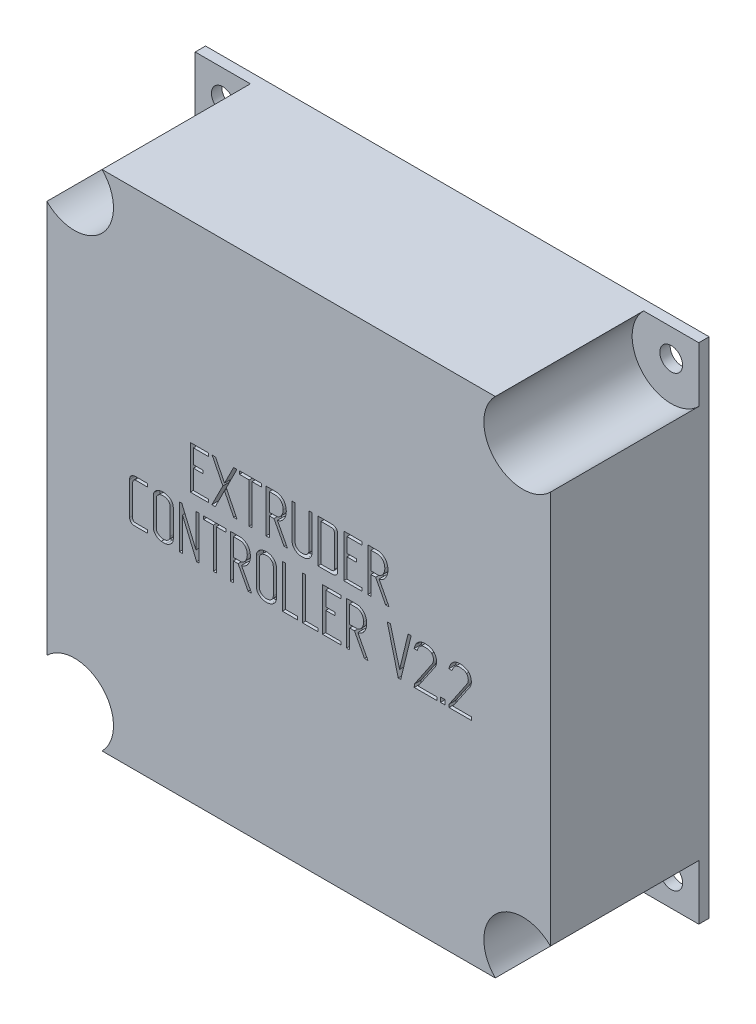
SolidWorks part; units mm, degrees
ref_plane "Front Plane" through (0, 0, 0) normal (0, 0, 1) x (1, 0, 0)
ref_plane "Top Plane" through (0, 0, 0) normal (0, 1, 0) x (1, 0, 0)
ref_plane "Right Plane" through (0, 0, 0) normal (1, 0, 0) x (0, 0, -1)
ref_plane "Plane1" through (0, 0, 23) normal (0, 0, 1) x (1, 0, 0)
sketch "Sketch1" plane through (0, 0, 23) normal (0, 0, 1) x (1, 0, 0)
  line L0 (32.2371, 36.0676) -> (32.2371, 45.1403)
  line L1 (32.2371, 45.1403) -> (11.9925, 45.1403)
  line L2 (11.9925, 45.1403) -> (11.9925, 36.0723)
  line L3 (11.9925, 36.0676) -> (32.2371, 36.0676)
  spline S0 degree 3 poles (11.9925, 36.0676) (11.9925, 36.0692) (11.9925, 36.0708) (11.9925, 36.0723) knots 0.369742 0.369742 0.369742 0.369742 0.369966 0.369966 0.369966 0.369966
extrude "Boss-Extrude1" add sketch "Sketch1" against normal blind 1
sketch "Sketch2" plane through (32.2371, 0, 0) normal (1, 0, 0) x (0, 0, -1)
  line L0 (-23, 36.0676) -> (-23, 45.1403)
  line L1 (-23, 45.1403) -> (-22, 45.1403)
  line L2 (-22, 45.1403) -> (-22, 36.0676)
  line L3 (-22, 36.0676) -> (-23, 36.0676)
extrude "Boss-Extrude2" add sketch "Sketch2" along normal blind 1.0059
sketch "Sketch3" plane through (0, 36.0676, 0) normal (0, -1, 0) x (1, 0, 0)
  line L0 (33.243, 22) -> (11.9925, 22)
  line L1 (11.9925, 22) -> (11.9925, 23)
  line L2 (11.9925, 23) -> (33.243, 23)
  line L3 (33.243, 23) -> (33.243, 22)
extrude "Boss-Extrude3" add sketch "Sketch3" along normal blind 4.7542
sketch "Sketch4" plane through (33.243, 0, 0) normal (1, 0, 0) x (0, 0, -1)
  line L0 (-23, 31.3134) -> (-23, 45.1403)
  line L1 (-23, 45.1403) -> (-22, 45.1403)
  line L2 (-22, 45.1403) -> (-22, 31.3134)
  line L3 (-22, 31.3134) -> (-23, 31.3134)
extrude "Boss-Extrude4" add sketch "Sketch4" along normal blind 20.0076
sketch "Sketch5" plane through (0, 31.3134, 0) normal (0, -1, 0) x (1, 0, 0)
  line L0 (11.9925, 22) -> (11.9925, 23)
  line L1 (11.9925, 23) -> (53.2506, 23)
  line L2 (53.2506, 23) -> (53.2506, 22)
  line L3 (53.2506, 22) -> (11.9925, 22)
extrude "Boss-Extrude5" add sketch "Sketch5" along normal blind 0.7109
sketch "Sketch6" plane through (0, 0, 22) normal (0, 0, -1) x (-1, 0, 0)
  line L0 (-53.2506, 45.1403) -> (-11.9925, 45.1403)
  line L1 (-11.9925, 45.1403) -> (-11.9925, 30.6025)
  line L2 (-11.9925, 30.6025) -> (-53.2506, 30.6025)
  line L3 (-53.2506, 30.6025) -> (-53.2506, 45.1403)
extrude "Boss-Extrude6" add sketch "Sketch6" along normal blind 22
sketch "Sketch7" plane through (0, 0, 23) normal (0, 0, 1) x (1, 0, 0)
  spline S0 degree 3 poles (32.2371, 41.6388) (32.2371, 41.7904) (32.2371, 41.9419) (32.2371, 42.0935) knots 0.441044 0.441044 0.441044 0.441044 0.460629 0.460629 0.460629 0.460629
  spline S1 degree 3 poles (32.919, 41.6388) (32.6917, 41.6388) (32.4644, 41.6388) (32.2371, 41.6388) knots 0.155394 0.155394 0.155394 0.155394 0.184772 0.184772 0.184772 0.184772
  spline S2 degree 3 poles (34.3747, 38.8919) (33.8895, 39.8075) (33.4042, 40.7232) (32.919, 41.6388) knots 0.02146 0.02146 0.02146 0.02146 0.155394 0.155394 0.155394 0.155394
  spline S3 degree 3 poles (34.8728, 38.8919) (34.7068, 38.8919) (34.5408, 38.8919) (34.3747, 38.8919) knots 0 0 0 0 0.02146 0.02146 0.02146 0.02146
  spline S4 degree 3 poles (33.4171, 41.6679) (33.9024, 40.7425) (34.3876, 39.8172) (34.8728, 38.8919) knots 0.86496 0.86496 0.86496 0.86496 1 1 1 1
  spline S5 degree 3 poles (33.243, 45.1403) (33.4075, 45.1403) (33.5671, 45.1064) (33.7267, 45.0387) (34.3732, 44.7644) (34.7036, 44.2262) (34.7036, 43.0123) (34.5875, 42.64) (34.3602, 42.3014) (34.1112, 41.9306) (33.7992, 41.7211) (33.4171, 41.6679) knots 0.654813 0.654813 0.654813 0.654813 0.676249 0.676249 0.676249 0.768188 0.768188 0.814433 0.814433 0.814433 0.86496 0.86496 0.86496 0.86496
  spline S6 degree 3 poles (32.2371, 45.1403) (32.5724, 45.1403) (32.9077, 45.1403) (33.243, 45.1403) knots 0.611475 0.611475 0.611475 0.611475 0.654813 0.654813 0.654813 0.654813
  spline S7 degree 3 poles (32.2371, 44.6857) (32.2371, 44.8372) (32.2371, 44.9888) (32.2371, 45.1403) knots 0.572305 0.572305 0.572305 0.572305 0.59189 0.59189 0.59189 0.59189
  spline S8 degree 3 poles (34.249, 43.4138) (34.249, 43.8103) (34.1329, 44.1295) (33.8911, 44.3762) (33.6923, 44.5789) (33.4703, 44.6857) (33.214, 44.6857) (32.8884, 44.6857) (32.5627, 44.6857) (32.2371, 44.6857) knots 0 0 0 0 0.128223 0.128223 0.128223 0.221431 0.221431 0.221431 0.340112 0.340112 0.340112 0.340112
  spline S9 degree 3 poles (32.2371, 42.0935) (32.5885, 42.0935) (32.94, 42.0935) (33.2914, 42.0935) (33.4848, 42.0935) (33.6831, 42.1999) (33.8814, 42.4175) (34.1209, 42.6803) (34.249, 43.0075) (34.249, 43.4138) knots 0.655283 0.655283 0.655283 0.655283 0.783468 0.783468 0.783468 0.867727 0.867727 0.867727 1 1 1 1
extrude "Cut-Extrude1" cut sketch "Sketch7" against normal blind 1
sketch "Sketch8" plane through (0, 0, 23) normal (0, 0, 1) x (1, 0, 0)
  spline S0 degree 3 poles (14.5558, 31.0571) (14.5558, 30.9104) (14.5558, 30.7637) (14.5558, 30.617) knots 0.97892 0.97892 0.97892 0.97892 1 1 1 1
  spline S1 degree 3 poles (14.5558, 36.4254) (14.0286, 36.4254) (13.5014, 36.4254) (12.9743, 36.4254) (12.6212, 36.4254) (12.4471, 36.2609) (12.4471, 35.9321) (12.4471, 34.4264) (12.4471, 32.9207) (12.4471, 31.415) (12.4471, 31.1732) (12.6164, 31.0571) (12.955, 31.0571) (13.4886, 31.0571) (14.0222, 31.0571) (14.5558, 31.0571) knots 0.536542 0.536542 0.536542 0.536542 0.612291 0.612291 0.612291 0.651988 0.651988 0.651988 0.868348 0.868348 0.868348 0.902244 0.902244 0.902244 0.97892 0.97892 0.97892 0.97892
  spline S2 degree 3 poles (14.5558, 36.88) (14.5558, 36.7284) (14.5558, 36.5769) (14.5558, 36.4254) knots 0.514767 0.514767 0.514767 0.514767 0.536542 0.536542 0.536542 0.536542
  spline S3 degree 3 poles (11.9925, 36.0723) (11.9925, 36.3238) (12.0748, 36.5173) (12.2392, 36.6575) (12.3126, 36.7202) (12.3988, 36.7639) (12.4762, 36.7978) (12.6094, 36.856) (12.7712, 36.88) (12.9695, 36.88) (13.4982, 36.88) (14.027, 36.88) (14.5558, 36.88) knots 0.369966 0.369966 0.369966 0.369966 0.401425 0.401425 0.401425 0.414663 0.414663 0.414663 0.438765 0.438765 0.438765 0.514767 0.514767 0.514767 0.514767
  spline S4 degree 3 poles (11.9925, 31.3134) (11.9925, 32.8997) (11.9925, 34.486) (11.9925, 36.0723) knots 0.142044 0.142044 0.142044 0.142044 0.369966 0.369966 0.369966 0.369966
  spline S5 degree 3 poles (14.5558, 30.617) (13.9561, 30.617) (13.3564, 30.617) (12.7567, 30.617) (12.5342, 30.617) (12.3553, 30.6751) (12.215, 30.796) (12.0668, 30.9237) (11.9925, 31.091) (11.9925, 31.3134) knots 0 0 0 0 0.086174 0.086174 0.086174 0.11411 0.11411 0.11411 0.142044 0.142044 0.142044 0.142044
extrude "Cut-Extrude2" cut sketch "Sketch8" against normal blind 1
sketch "Sketch9" plane through (0, 0, 23) normal (0, 0, 1) x (1, 0, 0)
  line L0 (16.5669, 30.6025) -> (17.2098, 30.6025)
  spline S0 degree 3 poles (16.5669, 30.6025) (16.3229, 30.6478) (16.0985, 30.7467) (15.8954, 30.9024) (15.5806, 31.1437) (15.4214, 31.444) (15.4214, 31.8019) (15.4214, 33.1012) (15.4214, 34.4006) (15.4214, 35.6999) (15.4214, 36.0917) (15.581, 36.406) (15.9051, 36.6382) (16.1701, 36.8281) (16.4999, 36.9187) (16.8917, 36.9235) (17.2591, 36.928) (17.5881, 36.8123) (17.8686, 36.5946) (18.1735, 36.358) (18.3232, 36.0578) (18.3232, 35.6999) (18.3232, 34.3974) (18.3232, 33.0948) (18.3232, 31.7922) (18.3232, 31.4295) (18.1733, 31.1297) (17.8686, 30.8975) (17.6705, 30.7466) (17.4504, 30.6479) (17.2098, 30.6025) knots 0.148508 0.148508 0.148508 0.148508 0.194373 0.194373 0.194373 0.259335 0.259335 0.259335 0.499077 0.499077 0.499077 0.566745 0.566745 0.566745 0.630921 0.630921 0.630921 0.695569 0.695569 0.695569 0.759663 0.759663 0.759663 1 1 1 1.064154 1.064154 1.064154 1.109535 1.109535 1.109535 1.109535
extrude "Cut-Extrude3" cut sketch "Sketch9" against normal blind 1
sketch "Sketch10" plane through (0, 0, 22) normal (0, 0, 1) x (1, 0, 0)
  spline S0 degree 3 poles (15.8615, 35.6129) (15.8615, 34.3683) (15.8615, 33.1238) (15.8615, 31.8793) (15.8615, 31.6133) (15.9921, 31.3957) (16.2533, 31.2312) (16.4667, 31.0968) (16.6837, 31.0281) (17.1383, 31.0281) (17.3511, 31.091) (17.5397, 31.2264) (17.7598, 31.3844) (17.8734, 31.5988) (17.8734, 31.8793) knots 0.500993 0.500993 0.500993 0.500993 0.780737 0.780737 0.780737 0.840202 0.840202 0.840202 0.890371 0.890371 0.942722 0.942722 0.942722 1 1 1 1
  spline S1 degree 3 poles (17.8734, 31.8793) (17.8734, 33.1222) (17.8734, 34.3651) (17.8734, 35.608) (17.8734, 35.8644) (17.7719, 36.0772) (17.5784, 36.2368) (17.3931, 36.3896) (17.1722, 36.4689) (16.6595, 36.4689) (16.4419, 36.4109) (16.2581, 36.2996) (15.9927, 36.139) (15.8615, 35.9127) (15.8615, 35.6129) knots 0 0 0 0 0.279396 0.279396 0.279396 0.333275 0.333275 0.333275 0.387883 0.387883 0.438519 0.438519 0.438519 0.500993 0.500993 0.500993 0.500993
extrude "Boss-Extrude7" add sketch "Sketch10" along normal blind 1
sketch "Sketch11" plane through (0, 0, 23) normal (0, 0, 1) x (1, 0, 0)
  spline S0 degree 3 poles (27.0381, 33.3785) (26.8866, 33.3785) (26.735, 33.3785) (26.5835, 33.3785) knots 0.302991 0.302991 0.302991 0.302991 0.322575 0.322575 0.322575 0.322575
  spline S1 degree 3 poles (27.72, 33.3785) (27.4927, 33.3785) (27.2654, 33.3785) (27.0381, 33.3785) knots 0.155276 0.155276 0.155276 0.155276 0.184653 0.184653 0.184653 0.184653
  spline S2 degree 3 poles (29.1806, 30.6315) (28.6937, 31.5472) (28.2069, 32.4629) (27.72, 33.3785) knots 0.021251 0.021251 0.021251 0.021251 0.155276 0.155276 0.155276 0.155276
  spline S3 degree 3 poles (29.6739, 30.6315) (29.5094, 30.6315) (29.345, 30.6315) (29.1806, 30.6315) knots 0 0 0 0 0.021251 0.021251 0.021251 0.021251
  spline S4 degree 3 poles (28.2182, 33.4075) (28.7034, 32.4822) (29.1886, 31.5569) (29.6739, 30.6315) knots 0.864966 0.864966 0.864966 0.864966 1 1 1 1
  spline S5 degree 3 poles (26.5835, 36.88) (27.0704, 36.88) (27.5572, 36.88) (28.0441, 36.88) (28.2085, 36.88) (28.3681, 36.8461) (28.5277, 36.7784) (29.1784, 36.5024) (29.5046, 35.9659) (29.5046, 34.752) (29.3885, 34.3796) (29.1661, 34.0411) (28.9193, 33.6656) (28.6002, 33.4607) (28.2182, 33.4075) knots 0.591754 0.591754 0.591754 0.591754 0.654673 0.654673 0.654673 0.676109 0.676109 0.676109 0.768003 0.768003 0.814225 0.814225 0.814225 0.864966 0.864966 0.864966 0.864966
  spline S6 degree 3 poles (26.5835, 33.3785) (26.5835, 34.5457) (26.5835, 35.7128) (26.5835, 36.88) knots 0.440914 0.440914 0.440914 0.440914 0.591754 0.591754 0.591754 0.591754
extrude "Cut-Extrude4" cut sketch "Sketch11" against normal blind 1
sketch "Sketch12" plane through (53.2506, 0, 0) normal (1, 0, 0) x (0, 0, -1)
  line L0 (-23, 30.6025) -> (-23, 45.1403)
  line L1 (-23, 45.1403) -> (0, 45.1403)
  line L2 (0, 45.1403) -> (0, 30.6025)
  line L3 (0, 30.6025) -> (-23, 30.6025)
extrude "Boss-Extrude8" add sketch "Sketch12" along normal blind 0.561
sketch "Sketch13" plane through (0, 0, 22) normal (0, 0, 1) x (1, 0, 0)
  spline S0 degree 3 poles (29.05, 35.1534) (29.05, 35.55) (28.9339, 35.8692) (28.697, 36.1158) (28.4979, 36.323) (28.2714, 36.4254) (28.015, 36.4254) (27.6894, 36.4254) (27.3638, 36.4254) (27.0381, 36.4254) knots 0 0 0 0 0.127832 0.127832 0.127832 0.221516 0.221516 0.221516 0.340204 0.340204 0.340204 0.340204
  spline S1 degree 3 poles (27.0381, 33.8331) (27.3896, 33.8331) (27.741, 33.8331) (28.0924, 33.8331) (28.2859, 33.8331) (28.4842, 33.9395) (28.6873, 34.1572) (28.9277, 34.4148) (29.05, 34.7472) (29.05, 35.1534) knots 0.655176 0.655176 0.655176 0.655176 0.783281 0.783281 0.783281 0.867942 0.867942 0.867942 1 1 1 1
  spline S2 degree 3 poles (27.0381, 36.4254) (27.0381, 35.5613) (27.0381, 34.6972) (27.0381, 33.8331) knots 0.340204 0.340204 0.340204 0.340204 0.655176 0.655176 0.655176 0.655176
extrude "Boss-Extrude9" add sketch "Sketch13" along normal blind 1
sketch "Sketch14" plane through (53.8116, 0, 0) normal (1, 0, 0) x (0, 0, -1)
  line L0 (-23, 30.6025) -> (-23, 45.1403)
  line L1 (-23, 45.1403) -> (0, 45.1403)
  line L2 (0, 45.1403) -> (0, 30.6025)
  line L3 (0, 30.6025) -> (-23, 30.6025)
extrude "Boss-Extrude10" add sketch "Sketch14" along normal blind 4.4832
sketch "Sketch15" plane through (0, 0, 23) normal (0, 0, 1) x (1, 0, 0)
  spline S0 degree 3 poles (43.8973, 33.3785) (43.7474, 33.3785) (43.5974, 33.3785) (43.4475, 33.3785) knots 0.303339 0.303339 0.303339 0.303339 0.322717 0.322717 0.322717 0.322717
  spline S1 degree 3 poles (44.584, 33.3785) (44.3551, 33.3785) (44.1262, 33.3785) (43.8973, 33.3785) knots 0.155402 0.155402 0.155402 0.155402 0.184989 0.184989 0.184989 0.184989
  spline S2 degree 3 poles (46.0398, 30.6315) (45.5545, 31.5472) (45.0693, 32.4629) (44.584, 33.3785) knots 0.021461 0.021461 0.021461 0.021461 0.155402 0.155402 0.155402 0.155402
  spline S3 degree 3 poles (46.5379, 30.6315) (46.3718, 30.6315) (46.2058, 30.6315) (46.0398, 30.6315) knots 0 0 0 0 0.021461 0.021461 0.021461 0.021461
  spline S4 degree 3 poles (45.0773, 33.4075) (45.5642, 32.4822) (46.051, 31.5569) (46.5379, 30.6315) knots 0.864857 0.864857 0.864857 0.864857 1 1 1 1
  spline S5 degree 3 poles (43.4475, 36.88) (43.9344, 36.88) (44.4212, 36.88) (44.9081, 36.88) (45.0677, 36.88) (45.2321, 36.8461) (45.3869, 36.7784) (46.0343, 36.4952) (46.3638, 35.9659) (46.3638, 34.752) (46.2526, 34.3796) (46.0252, 34.0411) (45.7748, 33.668) (45.4594, 33.4607) (45.0773, 33.4075) knots 0.591921 0.591921 0.591921 0.591921 0.654846 0.654846 0.654846 0.676082 0.676082 0.676082 0.767943 0.767943 0.814148 0.814148 0.814148 0.864857 0.864857 0.864857 0.864857
  spline S6 degree 3 poles (43.4475, 33.3785) (43.4475, 34.5457) (43.4475, 35.7128) (43.4475, 36.88) knots 0.441067 0.441067 0.441067 0.441067 0.591921 0.591921 0.591921 0.591921
extrude "Cut-Extrude5" cut sketch "Sketch15" against normal blind 1
sketch "Sketch16" plane through (0, 0, 23) normal (0, 0, 1) x (1, 0, 0)
  spline S0 degree 3 poles (53.8116, 30.6025) (53.6246, 30.6025) (53.4376, 30.6025) (53.2506, 30.6025) knots 0.104292 0.104292 0.104292 0.104292 0.125857 0.125857 0.125857 0.125857
  spline S1 degree 3 poles (53.8116, 31.0571) (53.8116, 30.9056) (53.8116, 30.7541) (53.8116, 30.6025) knots 0.982525 0.982525 0.982525 0.982525 1 1 1 1
  spline S2 degree 3 poles (56.3071, 34.723) (55.4753, 33.501) (54.6435, 32.2791) (53.8116, 31.0571) knots 0.707767 0.707767 0.707767 0.707767 0.878233 0.878233 0.878233 0.878233
  spline S3 degree 3 poles (53.2361, 35.463) (53.4537, 36.4157) (53.9857, 36.8945) (55.3447, 36.8945) (55.7413, 36.7687) (56.0266, 36.5318) (56.3329, 36.2774) (56.4812, 35.9031) (56.4812, 35.1583) (56.4232, 34.9261) (56.3071, 34.723) knots 0.492732 0.492732 0.492732 0.492732 0.579995 0.579995 0.632056 0.632056 0.632056 0.681711 0.681711 0.707767 0.707767 0.707767 0.707767
  spline S4 degree 3 poles (53.6859, 35.463) (53.5359, 35.463) (53.386, 35.463) (53.2361, 35.463) knots 0.475443 0.475443 0.475443 0.475443 0.492732 0.492732 0.492732 0.492732
  spline S5 degree 3 poles (55.8042, 36.1449) (55.7171, 36.2126) (55.6446, 36.2609) (55.5817, 36.29) (55.3716, 36.3869) (55.1271, 36.4399) (54.2662, 36.4399) (53.8793, 36.111) (53.6859, 35.463) knots 0.372872 0.372872 0.372872 0.372872 0.383102 0.383102 0.383102 0.413709 0.413709 0.475443 0.475443 0.475443 0.475443
  spline S6 degree 3 poles (53.27, 31.0378) (54.1244, 32.2968) (54.9788, 33.5559) (55.8332, 34.8149) (55.974, 35.0224) (56.0411, 35.2405) (56.0411, 35.6371) (56.0024, 35.8015) (55.9202, 35.9563) (55.8857, 36.0213) (55.8428, 36.082) (55.8042, 36.1449) knots 0.142604 0.142604 0.142604 0.142604 0.31807 0.31807 0.31807 0.345164 0.345164 0.364356 0.364356 0.364356 0.372872 0.372872 0.372872 0.372872
  spline S7 degree 3 poles (53.2506, 30.6025) (53.2571, 30.7476) (53.2635, 30.8927) (53.27, 31.0378) knots 0.125857 0.125857 0.125857 0.125857 0.142604 0.142604 0.142604 0.142604
extrude "Cut-Extrude6" cut sketch "Sketch16" against normal blind 1
sketch "Sketch17" plane through (58.2948, 0, 0) normal (1, 0, 0) x (0, 0, -1)
  line L0 (-23, 30.6025) -> (-23, 45.1403)
  line L1 (-23, 45.1403) -> (0, 45.1403)
  line L2 (0, 45.1403) -> (0, 30.6025)
  line L3 (0, 30.6025) -> (-23, 30.6025)
extrude "Boss-Extrude11" add sketch "Sketch17" along normal blind 0.561
sketch "Sketch18" plane through (32.2371, 0, 0) normal (1, 0, 0) x (0, 0, -1)
  line L0 (-23, 41.6388) -> (-22, 41.6388)
  line L1 (-22, 45.1403) -> (-23, 45.1403)
  spline S0 degree 3 poles (-22, 41.6388) (-22, 42.806) (-22, 43.9731) (-22, 45.1403) knots 0.441044 0.441044 0.441044 0.441044 0.59189 0.59189 0.59189 0.59189
  spline S1 degree 3 poles (-23, 41.6388) (-23, 42.806) (-23, 43.9731) (-23, 45.1403) knots 0.441044 0.441044 0.441044 0.441044 0.59189 0.59189 0.59189 0.59189
extrude "Cut-Extrude7" cut sketch "Sketch18" against normal blind 0.4546
sketch "Sketch19" plane through (58.8558, 0, 0) normal (1, 0, 0) x (0, 0, -1)
  line L0 (-23, 30.6025) -> (-23, 45.1403)
  line L1 (-23, 45.1403) -> (0, 45.1403)
  line L2 (0, 45.1403) -> (0, 30.6025)
  line L3 (0, 30.6025) -> (-23, 30.6025)
extrude "Boss-Extrude12" add sketch "Sketch19" along normal blind 2.6643
sketch "Sketch20" plane through (0, 0, 23) normal (0, 0, 1) x (1, 0, 0)
  line L0 (61.5201, 35.2825) -> (61.5201, 35.5705)
  spline S0 degree 3 poles (61.5201, 35.2825) (61.5034, 35.078) (61.4471, 34.8906) (61.3513, 34.723) knots 0.686264 0.686264 0.686264 0.686264 0.707767 0.707767 0.707767 0.707767
  spline S1 degree 3 poles (58.2803, 35.463) (58.4979, 36.4157) (59.0299, 36.8945) (60.3889, 36.8945) (60.7855, 36.7687) (61.0708, 36.5318) (61.3437, 36.3052) (61.4912, 35.9834) (61.5201, 35.5705) knots 0.492732 0.492732 0.492732 0.492732 0.579995 0.579995 0.632056 0.632056 0.632056 0.676289 0.676289 0.676289 0.676289
  spline S2 degree 3 poles (58.7301, 35.463) (58.5802, 35.463) (58.4302, 35.463) (58.2803, 35.463) knots 0.475443 0.475443 0.475443 0.475443 0.492732 0.492732 0.492732 0.492732
  spline S3 degree 3 poles (60.8484, 36.1449) (60.7613, 36.2126) (60.6888, 36.2609) (60.6259, 36.29) (60.4158, 36.3869) (60.1713, 36.4399) (59.3104, 36.4399) (58.9235, 36.111) (58.7301, 35.463) knots 0.372872 0.372872 0.372872 0.372872 0.383102 0.383102 0.383102 0.413709 0.413709 0.475443 0.475443 0.475443 0.475443
  spline S4 degree 3 poles (58.3142, 31.0378) (59.1686, 32.2968) (60.023, 33.5559) (60.8774, 34.8149) (61.0182, 35.0224) (61.0853, 35.2405) (61.0853, 35.6371) (61.0466, 35.8015) (60.9644, 35.9563) (60.9299, 36.0213) (60.8871, 36.082) (60.8484, 36.1449) knots 0.142604 0.142604 0.142604 0.142604 0.31807 0.31807 0.31807 0.345164 0.345164 0.364356 0.364356 0.364356 0.372872 0.372872 0.372872 0.372872
  spline S5 degree 3 poles (58.2948, 30.6025) (58.3013, 30.7476) (58.3077, 30.8927) (58.3142, 31.0378) knots 0.125857 0.125857 0.125857 0.125857 0.142604 0.142604 0.142604 0.142604
  spline S6 degree 3 poles (58.8558, 30.6025) (58.6688, 30.6025) (58.4818, 30.6025) (58.2948, 30.6025) knots 0.104292 0.104292 0.104292 0.104292 0.125857 0.125857 0.125857 0.125857
  spline S7 degree 3 poles (58.8558, 31.0571) (58.8558, 30.9056) (58.8558, 30.7541) (58.8558, 30.6025) knots 0.982525 0.982525 0.982525 0.982525 1 1 1 1
  spline S8 degree 3 poles (61.3513, 34.723) (60.5195, 33.501) (59.6877, 32.2791) (58.8558, 31.0571) knots 0.707767 0.707767 0.707767 0.707767 0.878233 0.878233 0.878233 0.878233
extrude "Cut-Extrude8" cut sketch "Sketch20" against normal blind 1
sketch "Sketch21" plane through (0, 45.1403, 0) normal (0, 1, 0) x (-1, 0, 0)
  line L0 (-11.9925, 0) -> (-61.5201, 0)
  line L1 (-61.5201, 0) -> (-61.5201, 23)
  line L2 (-61.5201, 23) -> (-11.9925, 23)
  line L3 (-11.9925, 23) -> (-11.9925, 0)
extrude "Boss-Extrude13" add sketch "Sketch21" along normal blind 27.8597
sketch "Sketch22" plane through (11.9925, 0, 0) normal (-1, 0, 0) x (0, 0, 1)
  line L0 (0, 30.6025) -> (0, 73)
  line L1 (0, 73) -> (23, 73)
  line L2 (23, 73) -> (23, 30.6025)
  line L3 (23, 30.6025) -> (0, 30.6025)
extrude "Boss-Extrude14" add sketch "Sketch22" along normal blind 11.9925
sketch "Sketch23" plane through (0, 30.6025, 0) normal (0, -1, 0) x (1, 0, 0)
  line L0 (61.5201, 0) -> (0, 0)
  line L1 (0, 0) -> (0, 23)
  line L2 (0, 23) -> (61.5201, 23)
  line L3 (61.5201, 23) -> (61.5201, 0)
extrude "Boss-Extrude15" add sketch "Sketch23" along normal blind 30.6025
sketch "Sketch24" plane through (61.5201, 0, 0) normal (1, 0, 0) x (0, 0, -1)
  line L0 (-23, 0) -> (-23, 73)
  line L1 (-23, 73) -> (0, 73)
  line L2 (0, 73) -> (0, 0)
  line L3 (0, 0) -> (-23, 0)
extrude "Boss-Extrude16" add sketch "Sketch24" along normal blind 11.4799
sketch "Sketch25" plane through (0, 41.6388, 0) normal (0, 1, 0) x (-1, 0, 0)
  line L0 (-32.2371, 23) -> (-32.2371, 22)
  line L1 (-31.7825, 22) -> (-31.7825, 23)
  spline S0 degree 3 poles (-32.2371, 23) (-32.0856, 23) (-31.934, 23) (-31.7825, 23) knots 0.303115 0.303115 0.303115 0.303115 0.3227 0.3227 0.3227 0.3227
  spline S1 degree 3 poles (-32.2371, 22) (-32.0856, 22) (-31.934, 22) (-31.7825, 22) knots 0.303115 0.303115 0.303115 0.303115 0.3227 0.3227 0.3227 0.3227
extrude "Cut-Extrude9" cut sketch "Sketch25" against normal blind 2.747
sketch "Sketch26" plane through (0, 33.3785, 0) normal (0, 1, 0) x (-1, 0, 0)
  line L0 (-27.0381, 23) -> (-27.0381, 22)
  line L1 (-26.5835, 22) -> (-26.5835, 23)
  spline S0 degree 3 poles (-27.0381, 23) (-26.8866, 23) (-26.735, 23) (-26.5835, 23) knots 0.302991 0.302991 0.302991 0.302991 0.322575 0.322575 0.322575 0.322575
  spline S1 degree 3 poles (-27.0381, 22) (-26.8866, 22) (-26.735, 22) (-26.5835, 22) knots 0.302991 0.302991 0.302991 0.302991 0.322575 0.322575 0.322575 0.322575
extrude "Cut-Extrude10" cut sketch "Sketch26" against normal blind 2.747
sketch "Sketch27" plane through (0, 33.3785, 0) normal (0, 1, 0) x (-1, 0, 0)
  line L0 (-43.8973, 23) -> (-43.8973, 22)
  line L1 (-43.4475, 22) -> (-43.4475, 23)
  spline S0 degree 3 poles (-43.8973, 23) (-43.7474, 23) (-43.5974, 23) (-43.4475, 23) knots 0.303339 0.303339 0.303339 0.303339 0.322717 0.322717 0.322717 0.322717
  spline S1 degree 3 poles (-43.8973, 22) (-43.7474, 22) (-43.5974, 22) (-43.4475, 22) knots 0.303339 0.303339 0.303339 0.303339 0.322717 0.322717 0.322717 0.322717
extrude "Cut-Extrude11" cut sketch "Sketch27" against normal blind 2.747
sketch "Sketch28" plane through (53.8116, 0, 0) normal (-1, 0, 0) x (0, 0, 1)
  line L0 (23, 31.0571) -> (22, 31.0571)
  line L1 (22, 30.6025) -> (23, 30.6025)
  spline S0 degree 3 poles (23, 31.0571) (23, 30.9056) (23, 30.7541) (23, 30.6025) knots 0.982525 0.982525 0.982525 0.982525 1 1 1 1
  spline S1 degree 3 poles (22, 31.0571) (22, 30.9056) (22, 30.7541) (22, 30.6025) knots 0.982525 0.982525 0.982525 0.982525 1 1 1 1
extrude "Cut-Extrude12" cut sketch "Sketch28" against normal blind 2.7131
sketch "Sketch29" plane through (58.8558, 0, 0) normal (-1, 0, 0) x (0, 0, 1)
  line L0 (23, 31.0571) -> (22, 31.0571)
  line L1 (22, 30.6025) -> (23, 30.6025)
  spline S0 degree 3 poles (23, 31.0571) (23, 30.9056) (23, 30.7541) (23, 30.6025) knots 0.982525 0.982525 0.982525 0.982525 1 1 1 1
  spline S1 degree 3 poles (22, 31.0571) (22, 30.9056) (22, 30.7541) (22, 30.6025) knots 0.982525 0.982525 0.982525 0.982525 1 1 1 1
extrude "Cut-Extrude13" cut sketch "Sketch29" against normal blind 2.7131
sketch "Sketch30" plane through (0, 0, 22) normal (0, 0, 1) x (1, 0, 0)
  spline S0 degree 3 poles (45.9092, 35.1534) (45.9092, 35.55) (45.7931, 35.8692) (45.5561, 36.1158) (45.3571, 36.323) (45.1305, 36.4254) (44.8742, 36.4254) (44.5486, 36.4254) (44.2229, 36.4254) (43.8973, 36.4254) knots 0 0 0 0 0.127831 0.127831 0.127831 0.221514 0.221514 0.221514 0.340201 0.340201 0.340201 0.340201
  spline S1 degree 3 poles (43.8973, 33.8331) (44.2487, 33.8331) (44.6002, 33.8331) (44.9516, 33.8331) (45.1499, 33.8331) (45.3482, 33.9395) (45.5465, 34.1572) (45.7837, 34.4176) (45.9092, 34.7472) (45.9092, 35.1534) knots 0.65517 0.65517 0.65517 0.65517 0.783273 0.783273 0.783273 0.868037 0.868037 0.868037 1 1 1 1
  spline S2 degree 3 poles (43.8973, 36.4254) (43.8973, 35.5613) (43.8973, 34.6972) (43.8973, 33.8331) knots 0.340201 0.340201 0.340201 0.340201 0.65517 0.65517 0.65517 0.65517
extrude "Boss-Extrude17" add sketch "Sketch30" along normal blind 1
sketch "Sketch31" plane through (0, 0, 23) normal (0, 0, 1) x (1, 0, 0)
  spline S0 degree 3 poles (41.5711, 45.0968) (41.9531, 44.9952) (42.1417, 44.7389) (42.1417, 44.3326) (42.1417, 42.7157) (42.1417, 41.0988) (42.1417, 39.4819) knots 0.665783 0.665783 0.665783 0.665783 0.724817 0.724817 0.724817 1 1 1 1
  spline S1 degree 3 poles (39.2787, 45.1403) (39.9074, 45.1403) (40.5361, 45.1403) (41.1648, 45.1403) (41.3776, 45.1403) (41.513, 45.1258) (41.5711, 45.0968) knots 0.535474 0.535474 0.535474 0.535474 0.642474 0.642474 0.642474 0.665783 0.665783 0.665783 0.665783
  spline S2 degree 3 poles (39.2787, 38.8773) (39.2787, 40.965) (39.2787, 43.0526) (39.2787, 45.1403) knots 0.180178 0.180178 0.180178 0.180178 0.535474 0.535474 0.535474 0.535474
  spline S3 degree 3 poles (42.1417, 39.4819) (42.1417, 39.2981) (42.0547, 39.153) (41.8854, 39.0369) (41.7338, 38.933) (41.5662, 38.8773) (41.3776, 38.8773) (40.678, 38.8773) (39.9783, 38.8773) (39.2787, 38.8773) knots 0 0 0 0 0.03043 0.03043 0.03043 0.061126 0.061126 0.061126 0.180178 0.180178 0.180178 0.180178
extrude "Cut-Extrude14" cut sketch "Sketch31" against normal blind 1
sketch "Sketch32" plane through (0, 0, 22) normal (0, 0, 1) x (1, 0, 0)
  spline S0 degree 3 poles (39.7333, 39.3174) (40.2169, 39.3174) (40.7005, 39.3174) (41.1842, 39.3174) (41.5179, 39.3174) (41.6871, 39.4335) (41.6871, 39.6753) knots 0.849313 0.849313 0.849313 0.849313 0.95081 0.95081 0.95081 1 1 1 1
  spline S1 degree 3 poles (39.7333, 44.6857) (39.7333, 42.8963) (39.7333, 41.1069) (39.7333, 39.3174) knots 0.473775 0.473775 0.473775 0.473775 0.849313 0.849313 0.849313 0.849313
  spline S2 degree 3 poles (41.6871, 39.6753) (41.6871, 41.181) (41.6871, 42.6867) (41.6871, 44.1924) (41.6871, 44.5213) (41.513, 44.6857) (41.16, 44.6857) (40.6844, 44.6857) (40.2088, 44.6857) (39.7333, 44.6857) knots 0 0 0 0 0.315993 0.315993 0.315993 0.37397 0.37397 0.37397 0.473775 0.473775 0.473775 0.473775
extrude "Boss-Extrude18" add sketch "Sketch32" along normal blind 1
sketch "Sketch33" plane through (0, 0, 23) normal (0, 0, 1) x (1, 0, 0)
  spline S0 degree 3 poles (49.6089, 38.8919) (49.4429, 38.8919) (49.2768, 38.8919) (49.1108, 38.8919) knots 0 0 0 0 0.02146 0.02146 0.02146 0.02146
  spline S1 degree 3 poles (48.1532, 41.6679) (48.6384, 40.7425) (49.1237, 39.8172) (49.6089, 38.8919) knots 0.86496 0.86496 0.86496 0.86496 1 1 1 1
  spline S2 degree 3 poles (46.5185, 45.1403) (47.0054, 45.1403) (47.4922, 45.1403) (47.9791, 45.1403) (48.1435, 45.1403) (48.3031, 45.1064) (48.4627, 45.0387) (49.1093, 44.7644) (49.4396, 44.2262) (49.4396, 43.0123) (49.3236, 42.64) (49.0963, 42.3014) (48.8473, 41.9306) (48.5353, 41.7211) (48.1532, 41.6679) knots 0.59189 0.59189 0.59189 0.59189 0.654813 0.654813 0.654813 0.676249 0.676249 0.676249 0.768188 0.768188 0.814433 0.814433 0.814433 0.86496 0.86496 0.86496 0.86496
  spline S3 degree 3 poles (46.5185, 38.8919) (46.5185, 40.9747) (46.5185, 43.0575) (46.5185, 45.1403) knots 0.3227 0.3227 0.3227 0.3227 0.59189 0.59189 0.59189 0.59189
  spline S4 degree 3 poles (46.9732, 38.8919) (46.8216, 38.8919) (46.6701, 38.8919) (46.5185, 38.8919) knots 0.303115 0.303115 0.303115 0.303115 0.3227 0.3227 0.3227 0.3227
  spline S5 degree 3 poles (46.9732, 41.6388) (46.9732, 40.7232) (46.9732, 39.8075) (46.9732, 38.8919) knots 0.184772 0.184772 0.184772 0.184772 0.303115 0.303115 0.303115 0.303115
  spline S6 degree 3 poles (47.6551, 41.6388) (47.4278, 41.6388) (47.2005, 41.6388) (46.9732, 41.6388) knots 0.155394 0.155394 0.155394 0.155394 0.184772 0.184772 0.184772 0.184772
  spline S7 degree 3 poles (49.1108, 38.8919) (48.6255, 39.8075) (48.1403, 40.7232) (47.6551, 41.6388) knots 0.02146 0.02146 0.02146 0.02146 0.155394 0.155394 0.155394 0.155394
extrude "Cut-Extrude15" cut sketch "Sketch33" against normal blind 1
sketch "Sketch34" plane through (0, 0, 22) normal (0, 0, 1) x (1, 0, 0)
  spline S0 degree 3 poles (46.9732, 42.0935) (47.3246, 42.0935) (47.676, 42.0935) (48.0275, 42.0935) (48.2209, 42.0935) (48.4192, 42.1999) (48.6175, 42.4175) (48.857, 42.6803) (48.985, 43.0075) (48.985, 43.4138) knots 0.655269 0.655269 0.655269 0.655269 0.78346 0.78346 0.78346 0.867722 0.867722 0.867722 1 1 1 1
  spline S1 degree 3 poles (46.9732, 44.6857) (46.9732, 43.8216) (46.9732, 42.9575) (46.9732, 42.0935) knots 0.340085 0.340085 0.340085 0.340085 0.655269 0.655269 0.655269 0.655269
  spline S2 degree 3 poles (48.985, 43.4138) (48.985, 43.8103) (48.8641, 44.1295) (48.6272, 44.3762) (48.4304, 44.581) (48.2064, 44.6857) (47.9501, 44.6857) (47.6244, 44.6857) (47.2988, 44.6857) (46.9732, 44.6857) knots 0 0 0 0 0.128122 0.128122 0.128122 0.221363 0.221363 0.221363 0.340085 0.340085 0.340085 0.340085
extrude "Boss-Extrude19" add sketch "Sketch34" along normal blind 1
sketch "Sketch35" plane through (0, 0, 23) normal (0, 0, 1) x (1, 0, 0)
  spline S0 degree 3 poles (30.3703, 35.6999) (30.3703, 36.0917) (30.5299, 36.406) (30.8539, 36.6382) (31.119, 36.8281) (31.4488, 36.9187) (31.8357, 36.9235) (32.208, 36.9282) (32.5321, 36.8123) (32.8174, 36.5946) (33.1243, 36.3606) (33.272, 36.0578) (33.272, 35.6999) (33.272, 34.3974) (33.272, 33.0948) (33.272, 31.7922) knots 0.499071 0.499071 0.499071 0.499071 0.566736 0.566736 0.566736 0.630618 0.630618 0.630618 0.695537 0.695537 0.695537 0.759638 0.759638 0.759638 1 1 1 1
  spline S1 degree 3 poles (33.272, 31.7922) (33.272, 31.4295) (33.1221, 31.1297) (32.8174, 30.8975) (32.532, 30.68) (32.2081, 30.5735) (31.4681, 30.5735) (31.1344, 30.6799) (30.8442, 30.9024) (30.5295, 31.1437) (30.3703, 31.444) (30.3703, 31.8019) (30.3703, 33.1012) (30.3703, 34.4006) (30.3703, 35.6999) knots 0 0 0 0 0.064152 0.064152 0.064152 0.12969 0.12969 0.194377 0.194377 0.194377 0.259336 0.259336 0.259336 0.499071 0.499071 0.499071 0.499071
extrude "Cut-Extrude16" cut sketch "Sketch35" against normal blind 1
sketch "Sketch36" plane through (0, 0, 22) normal (0, 0, 1) x (1, 0, 0)
  spline S0 degree 3 poles (30.8056, 35.6129) (30.8056, 34.3683) (30.8056, 33.1238) (30.8056, 31.8793) (30.8056, 31.6133) (30.9361, 31.3957) (31.1973, 31.2312) (31.4107, 31.0968) (31.6277, 31.0281) (32.0872, 31.0281) (32.3, 31.091) (32.4886, 31.2264) (32.7087, 31.3844) (32.8174, 31.5988) (32.8174, 31.8793) knots 0.500912 0.500912 0.500912 0.500912 0.780616 0.780616 0.780616 0.840072 0.840072 0.840072 0.890947 0.890947 0.942906 0.942906 0.942906 1 1 1 1
  spline S1 degree 3 poles (32.8174, 31.8793) (32.8174, 33.1222) (32.8174, 34.3651) (32.8174, 35.608) (32.8174, 35.8644) (32.7207, 36.0772) (32.5273, 36.2368) (32.3419, 36.3896) (32.121, 36.4689) (31.6084, 36.4689) (31.3907, 36.4109) (31.2021, 36.2996) (30.9385, 36.1442) (30.8056, 35.9127) (30.8056, 35.6129) knots 0 0 0 0 0.279282 0.279282 0.279282 0.332989 0.332989 0.332989 0.387747 0.387747 0.438522 0.438522 0.438522 0.500912 0.500912 0.500912 0.500912
extrude "Boss-Extrude20" add sketch "Sketch36" along normal blind 1
sketch "Sketch37" plane through (0, 0, 23) normal (0, 0, 1) x (1, 0, 0)
  spline S0 degree 1 poles (23.4254, 38.8919) (20.7897, 38.8919) knots 0 0 0.106114 0.106114
  spline S1 degree 1 poles (23.4254, 39.3174) (23.4254, 38.8919) knots 0.982866 0.982866 1 1
  spline S2 degree 1 poles (21.2395, 39.3174) (23.4254, 39.3174) knots 0.89486 0.89486 0.982866 0.982866
  spline S3 degree 1 poles (21.2395, 42.1225) (21.2395, 39.3174) knots 0.781931 0.781931 0.89486 0.89486
  spline S4 degree 1 poles (22.6033, 42.1225) (21.2395, 42.1225) knots 0.727025 0.727025 0.781931 0.781931
  spline S5 degree 1 poles (22.6033, 42.5626) (22.6033, 42.1225) knots 0.709307 0.709307 0.727025 0.727025
  spline S6 degree 1 poles (21.2395, 42.5626) (22.6033, 42.5626) knots 0.6544 0.6544 0.709307 0.709307
  spline S7 degree 1 poles (21.2395, 44.6712) (21.2395, 42.5626) knots 0.569509 0.569509 0.6544 0.6544
  spline S8 degree 1 poles (23.4254, 44.6712) (21.2395, 44.6712) knots 0.481503 0.481503 0.569509 0.569509
  spline S9 degree 1 poles (23.4254, 45.1258) (23.4254, 44.6712) knots 0.463201 0.463201 0.481503 0.481503
  spline S10 degree 1 poles (20.7897, 45.1258) (23.4254, 45.1258) knots 0.357087 0.357087 0.463201 0.463201
  spline S11 degree 1 poles (20.7897, 38.8919) (20.7897, 45.1258) knots 0.106114 0.106114 0.357087 0.357087
extrude "Cut-Extrude17" cut sketch "Sketch37" against normal blind 1
sketch "Sketch38" plane through (0, 0, 23) normal (0, 0, 1) x (1, 0, 0)
  spline S0 degree 1 poles (27.5508, 45.1258) (26.008, 42.0403) knots 0 0 0.124226 0.124226
  spline S1 degree 1 poles (27.0768, 45.1258) (27.5508, 45.1258) knots 0.982933 0.982933 1 1
  spline S2 degree 1 poles (25.7468, 42.4997) (27.0768, 45.1258) knots 0.87693 0.87693 0.982933 0.982933
  spline S3 degree 1 poles (24.4556, 45.1258) (25.7468, 42.4997) knots 0.771549 0.771549 0.87693 0.87693
  spline S4 degree 1 poles (23.9623, 45.1258) (24.4556, 45.1258) knots 0.753785 0.753785 0.771549 0.771549
  spline S5 degree 1 poles (25.5099, 42.0257) (23.9623, 45.1258) knots 0.629014 0.629014 0.753785 0.753785
  spline S6 degree 1 poles (23.9187, 38.8773) (25.5099, 42.0257) knots 0.501982 0.501982 0.629014 0.629014
  spline S7 degree 1 poles (24.412, 38.8773) (23.9187, 38.8773) knots 0.484218 0.484218 0.501982 0.501982
  spline S8 degree 1 poles (25.7468, 41.5518) (24.412, 38.8773) knots 0.376581 0.376581 0.484218 0.484218
  spline S9 degree 1 poles (27.0768, 38.8773) (25.7468, 41.5518) knots 0.269022 0.269022 0.376581 0.376581
  spline S10 degree 1 poles (27.5701, 38.8773) (27.0768, 38.8773) knots 0.251258 0.251258 0.269022 0.269022
  spline S11 degree 1 poles (26.008, 42.0403) (27.5701, 38.8773) knots 0.124226 0.124226 0.251258 0.251258
extrude "Cut-Extrude18" cut sketch "Sketch38" against normal blind 1
sketch "Sketch39" plane through (0, 0, 23) normal (0, 0, 1) x (1, 0, 0)
  spline S0 degree 1 poles (45.6819, 38.8919) (43.0461, 38.8919) knots 0 0 0.106196 0.106196
  spline S1 degree 1 poles (45.6819, 39.3174) (45.6819, 38.8919) knots 0.982853 0.982853 1 1
  spline S2 degree 1 poles (43.5007, 39.3174) (45.6819, 39.3174) knots 0.894973 0.894973 0.982853 0.982853
  spline S3 degree 1 poles (43.5007, 42.1225) (43.5007, 39.3174) knots 0.781956 0.781956 0.894973 0.894973
  spline S4 degree 1 poles (44.8597, 42.1225) (43.5007, 42.1225) knots 0.727202 0.727202 0.781956 0.781956
  spline S5 degree 1 poles (44.8597, 42.5626) (44.8597, 42.1225) knots 0.70947 0.70947 0.727202 0.727202
  spline S6 degree 1 poles (43.5007, 42.5626) (44.8597, 42.5626) knots 0.654716 0.654716 0.70947 0.70947
  spline S7 degree 1 poles (43.5007, 44.6712) (43.5007, 42.5626) knots 0.569758 0.569758 0.654716 0.654716
  spline S8 degree 1 poles (45.6819, 44.6712) (43.5007, 44.6712) knots 0.481878 0.481878 0.569758 0.569758
  spline S9 degree 1 poles (45.6819, 45.1258) (45.6819, 44.6712) knots 0.463562 0.463562 0.481878 0.481878
  spline S10 degree 1 poles (43.0461, 45.1258) (45.6819, 45.1258) knots 0.357366 0.357366 0.463562 0.463562
  spline S11 degree 1 poles (43.0461, 38.8919) (43.0461, 45.1258) knots 0.106196 0.106196 0.357366 0.357366
extrude "Cut-Extrude19" cut sketch "Sketch39" against normal blind 1
sketch "Sketch40" plane through (0, 0, 23) normal (0, 0, 1) x (1, 0, 0)
  spline S0 degree 1 poles (42.6109, 30.6315) (39.9751, 30.6315) knots 0 0 0.106196 0.106196
  spline S1 degree 1 poles (42.6109, 31.0571) (42.6109, 30.6315) knots 0.982853 0.982853 1 1
  spline S2 degree 1 poles (40.4297, 31.0571) (42.6109, 31.0571) knots 0.894973 0.894973 0.982853 0.982853
  spline S3 degree 1 poles (40.4297, 33.8622) (40.4297, 31.0571) knots 0.781956 0.781956 0.894973 0.894973
  spline S4 degree 1 poles (41.7887, 33.8622) (40.4297, 33.8622) knots 0.727202 0.727202 0.781956 0.781956
  spline S5 degree 1 poles (41.7887, 34.3023) (41.7887, 33.8622) knots 0.70947 0.70947 0.727202 0.727202
  spline S6 degree 1 poles (40.4297, 34.3023) (41.7887, 34.3023) knots 0.654716 0.654716 0.70947 0.70947
  spline S7 degree 1 poles (40.4297, 36.4109) (40.4297, 34.3023) knots 0.569758 0.569758 0.654716 0.654716
  spline S8 degree 1 poles (42.6109, 36.4109) (40.4297, 36.4109) knots 0.481878 0.481878 0.569758 0.569758
  spline S9 degree 1 poles (42.6109, 36.8655) (42.6109, 36.4109) knots 0.463562 0.463562 0.481878 0.481878
  spline S10 degree 1 poles (39.9751, 36.8655) (42.6109, 36.8655) knots 0.357366 0.357366 0.463562 0.463562
  spline S11 degree 1 poles (39.9751, 30.6315) (39.9751, 36.8655) knots 0.106196 0.106196 0.357366 0.357366
extrude "Cut-Extrude20" cut sketch "Sketch40" against normal blind 1
sketch "Sketch41" plane through (0, 0, 23) normal (0, 0, 1) x (1, 0, 0)
  spline S0 degree 1 poles (22.081, 30.617) (21.7086, 30.617) knots 0 0 0.010837 0.010837
  spline S1 degree 1 poles (22.081, 36.88) (22.081, 30.617) knots 0.817743 0.817743 1 1
  spline S2 degree 1 poles (21.6118, 36.88) (22.081, 36.88) knots 0.804091 0.804091 0.817743 0.817743
  spline S3 degree 1 poles (21.6118, 32.0437) (21.6118, 36.88) knots 0.663353 0.663353 0.804091 0.804091
  spline S4 degree 1 poles (19.5613, 36.8751) (21.6118, 32.0437) knots 0.510615 0.510615 0.663353 0.663353
  spline S5 degree 1 poles (19.2034, 36.88) (19.5613, 36.8751) knots 0.500199 0.500199 0.510615 0.510615
  spline S6 degree 1 poles (19.2034, 30.617) (19.2034, 36.88) knots 0.317943 0.317943 0.500199 0.500199
  spline S7 degree 1 poles (19.658, 30.617) (19.2034, 30.617) knots 0.304713 0.304713 0.317943 0.317943
  spline S8 degree 1 poles (19.658, 35.4581) (19.658, 30.617) knots 0.163834 0.163834 0.304713 0.304713
  spline S9 degree 1 poles (21.7086, 30.617) (19.658, 35.4581) knots 0.010837 0.010837 0.163834 0.163834
extrude "Cut-Extrude21" cut sketch "Sketch41" against normal blind 1
sketch "Sketch42" plane through (0, 0, 23) normal (0, 0, 1) x (1, 0, 0)
  spline S0 degree 1 poles (31.1296, 44.6857) (29.7561, 44.6857) knots 0 0 0.072449 0.072449
  spline S1 degree 1 poles (31.1296, 45.1403) (31.1296, 44.6857) knots 0.97602 0.97602 1 1
  spline S2 degree 1 poles (27.9135, 45.1403) (31.1296, 45.1403) knots 0.806378 0.806378 0.97602 0.97602
  spline S3 degree 1 poles (27.9135, 44.6857) (27.9135, 45.1403) knots 0.782398 0.782398 0.806378 0.806378
  spline S4 degree 1 poles (29.316, 44.6857) (27.9135, 44.6857) knots 0.708418 0.708418 0.782398 0.782398
  spline S5 degree 1 poles (29.316, 38.8773) (29.316, 44.6857) knots 0.402041 0.402041 0.708418 0.708418
  spline S6 degree 1 poles (29.7561, 38.8773) (29.316, 38.8773) knots 0.378827 0.378827 0.402041 0.402041
  spline S7 degree 1 poles (29.7561, 44.6857) (29.7561, 38.8773) knots 0.072449 0.072449 0.378827 0.378827
extrude "Cut-Extrude22" cut sketch "Sketch42" against normal blind 1
sketch "Sketch43" plane through (0, 0, 23) normal (0, 0, 1) x (1, 0, 0)
  spline S0 degree 1 poles (25.9355, 36.4254) (24.5571, 36.4254) knots 0 0 0.072704 0.072704
  spline S1 degree 1 poles (25.9355, 36.88) (25.9355, 36.4254) knots 0.97602 0.97602 1 1
  spline S2 degree 1 poles (22.7193, 36.88) (25.9355, 36.88) knots 0.806378 0.806378 0.97602 0.97602
  spline S3 degree 1 poles (22.7193, 36.4254) (22.7193, 36.88) knots 0.782398 0.782398 0.806378 0.806378
  spline S4 degree 1 poles (24.1219, 36.4254) (22.7193, 36.4254) knots 0.708418 0.708418 0.782398 0.782398
  spline S5 degree 1 poles (24.1219, 30.617) (24.1219, 36.4254) knots 0.402041 0.402041 0.708418 0.708418
  spline S6 degree 1 poles (24.5571, 30.617) (24.1219, 30.617) knots 0.379082 0.379082 0.402041 0.402041
  spline S7 degree 1 poles (24.5571, 36.4254) (24.5571, 30.617) knots 0.072704 0.072704 0.379082 0.379082
extrude "Cut-Extrude23" cut sketch "Sketch43" against normal blind 1
sketch "Sketch44" plane through (0, 0, 23) normal (0, 0, 1) x (1, 0, 0)
  spline S0 degree 1 poles (52.8105, 36.88) (51.2968, 30.6315) knots 0 0 0.261119 0.261119
  spline S1 degree 1 poles (52.3607, 36.88) (52.8105, 36.88) knots 0.981733 0.981733 1 1
  spline S2 degree 1 poles (51.1323, 31.8019) (52.3607, 36.88) knots 0.76954 0.76954 0.981733 0.981733
  spline S3 degree 1 poles (49.7927, 36.88) (51.1323, 31.8019) knots 0.55624 0.55624 0.76954 0.76954
  spline S4 degree 1 poles (49.3381, 36.88) (49.7927, 36.88) knots 0.537776 0.537776 0.55624 0.55624
  spline S5 degree 1 poles (50.934, 30.6315) (49.3381, 36.88) knots 0.275851 0.275851 0.537776 0.537776
  spline S6 degree 1 poles (51.2968, 30.6315) (50.934, 30.6315) knots 0.261119 0.261119 0.275851 0.275851
extrude "Cut-Extrude24" cut sketch "Sketch44" against normal blind 1
sketch "Sketch45" plane through (0, 0, 23) normal (0, 0, 1) x (1, 0, 0)
  spline S0 degree 1 poles (36.3624, 30.617) (34.1522, 30.617) knots 0 0 0.130422 0.130422
  spline S1 degree 1 poles (36.3624, 31.0716) (36.3624, 30.617) knots 0.973174 0.973174 1 1
  spline S2 degree 1 poles (34.6069, 31.0716) (36.3624, 31.0716) knots 0.869578 0.869578 0.973174 0.973174
  spline S3 degree 1 poles (34.6069, 36.88) (34.6069, 31.0716) knots 0.526826 0.526826 0.869578 0.869578
  spline S4 degree 1 poles (34.1522, 36.88) (34.6069, 36.88) knots 0.5 0.5 0.526826 0.526826
  spline S5 degree 1 poles (34.1522, 30.617) (34.1522, 36.88) knots 0.130422 0.130422 0.5 0.5
extrude "Cut-Extrude25" cut sketch "Sketch45" against normal blind 1
sketch "Sketch46" plane through (0, 0, 23) normal (0, 0, 1) x (1, 0, 0)
  spline S0 degree 1 poles (39.2787, 30.617) (37.0685, 30.617) knots 0 0 0.130422 0.130422
  spline S1 degree 1 poles (39.2787, 31.0716) (39.2787, 30.617) knots 0.973174 0.973174 1 1
  spline S2 degree 1 poles (37.5231, 31.0716) (39.2787, 31.0716) knots 0.869578 0.869578 0.973174 0.973174
  spline S3 degree 1 poles (37.5231, 36.88) (37.5231, 31.0716) knots 0.526826 0.526826 0.869578 0.869578
  spline S4 degree 1 poles (37.0685, 36.88) (37.5231, 36.88) knots 0.5 0.5 0.526826 0.526826
  spline S5 degree 1 poles (37.0685, 30.617) (37.0685, 36.88) knots 0.130422 0.130422 0.5 0.5
extrude "Cut-Extrude26" cut sketch "Sketch46" against normal blind 1
sketch "Sketch47" plane through (0, 0, 23) normal (0, 0, 1) x (1, 0, 0)
  spline S0 degree 3 poles (38.442, 45.1403) (38.442, 43.4798) (38.442, 41.8194) (38.442, 40.159) (38.442, 39.7479) (38.3018, 39.4287) (38.0261, 39.1965) (37.7637, 38.9756) (37.4264, 38.8628) (36.6236, 38.8628) (36.2947, 38.9644) (36.0239, 39.1724) (35.6986, 39.4222) (35.5354, 39.7575) (35.5354, 40.1735) (35.5354, 41.8291) (35.5354, 43.4847) (35.5354, 45.1403) knots 0 0 0 0 0.177214 0.177214 0.177214 0.215812 0.215812 0.215812 0.255355 0.255355 0.292139 0.292139 0.292139 0.333299 0.333299 0.333299 0.51001 0.51001 0.51001 0.51001
  spline S1 degree 3 poles (37.9874, 45.1403) (38.1389, 45.1403) (38.2905, 45.1403) (38.442, 45.1403) knots 0.983827 0.983827 0.983827 0.983827 1 1 1 1
  spline S2 degree 3 poles (35.99, 45.1403) (35.99, 43.4895) (35.99, 41.8387) (35.99, 40.188) (35.99, 39.8978) (36.1158, 39.6753) (36.3721, 39.5157) (36.5792, 39.3868) (36.7928, 39.3174) (37.262, 39.3174) (37.4748, 39.3803) (37.6537, 39.5109) (37.8726, 39.6706) (37.9874, 39.8881) (37.9874, 40.1783) (37.9874, 41.8323) (37.9874, 43.4863) (37.9874, 45.1403) knots 0.526183 0.526183 0.526183 0.526183 0.702364 0.702364 0.702364 0.731235 0.731235 0.731235 0.75519 0.75519 0.779645 0.779645 0.779645 0.807344 0.807344 0.807344 0.983827 0.983827 0.983827 0.983827
  spline S3 degree 3 poles (35.5354, 45.1403) (35.687, 45.1403) (35.8385, 45.1403) (35.99, 45.1403) knots 0.51001 0.51001 0.51001 0.51001 0.526183 0.526183 0.526183 0.526183
extrude "Cut-Extrude27" cut sketch "Sketch47" against normal blind 1
sketch "Sketch48" plane through (0, 0, 23) normal (0, 0, 1) x (1, 0, 0)
  spline S0 degree 1 poles (57.7435, 30.6315) (57.0616, 30.6315) knots 0 0 0.25089 0.25089
  spline S1 degree 1 poles (57.7435, 31.3086) (57.7435, 30.6315) knots 0.75089 0.75089 1 1
  spline S2 degree 1 poles (57.0616, 31.3086) (57.7435, 31.3086) knots 0.5 0.5 0.75089 0.75089
  spline S3 degree 1 poles (57.0616, 30.6315) (57.0616, 31.3086) knots 0.25089 0.25089 0.5 0.5
extrude "Cut-Extrude28" cut sketch "Sketch48" against normal blind 1
hole_wizard "Hole1" positions "Sketch50" profile "Sketch49" legacy
sketch "Sketch50" plane through (0, 0, 23) normal (0, 0, 1) x (1, 0, 0)
  point P0 (4, 69)
sketch "Sketch49" plane through (4, 69, 23) normal (1, 0, 0) x (0, -1, 0)
  line L0 (0, 0) -> (0, 23)
  line L1 (0, 23) -> (1.65, 23)
  line L2 (1.65, 23) -> (1.65, 21.5)
  line L3 (1.65, 21.5) -> (5.6569, 21.5)
  line L4 (5.6569, 21.5) -> (5.6569, 0)
  line L5 (5.6569, 0) -> (0, 0)
  line L6 (0, 110) -> (0, -10) construction
  dimension "Diameter" = 3.3
  dimension "Depth" = 23
  dimension "C-Bore Diameter" = 11.3137
  dimension "C-Bore Depth" = 21.5
hole_wizard "Hole2" positions "Sketch52" profile "Sketch51" legacy
sketch "Sketch52" plane through (0, 0, 23) normal (0, 0, 1) x (1, 0, 0)
  point P0 (4, 4)
sketch "Sketch51" plane through (4, 4, 23) normal (1, 0, 0) x (0, -1, 0)
  line L0 (0, 0) -> (0, 23)
  line L1 (0, 23) -> (1.65, 23)
  line L2 (1.65, 23) -> (1.65, 21.5)
  line L3 (1.65, 21.5) -> (5.6569, 21.5)
  line L4 (5.6569, 21.5) -> (5.6569, 0)
  line L5 (5.6569, 0) -> (0, 0)
  line L6 (0, 110) -> (0, -10) construction
  dimension "Diameter" = 3.3
  dimension "Depth" = 23
  dimension "C-Bore Diameter" = 11.3137
  dimension "C-Bore Depth" = 21.5
hole_wizard "Hole3" positions "Sketch54" profile "Sketch53" legacy
sketch "Sketch54" plane through (0, 0, 23) normal (0, 0, 1) x (1, 0, 0)
  point P0 (69, 4)
sketch "Sketch53" plane through (69, 4, 23) normal (1, 0, 0) x (0, -1, 0)
  line L0 (0, 0) -> (0, 23)
  line L1 (0, 23) -> (1.65, 23)
  line L2 (1.65, 23) -> (1.65, 21.5)
  line L3 (1.65, 21.5) -> (5.6569, 21.5)
  line L4 (5.6569, 21.5) -> (5.6569, 0)
  line L5 (5.6569, 0) -> (0, 0)
  line L6 (0, 110) -> (0, -10) construction
  dimension "Diameter" = 3.3
  dimension "Depth" = 23
  dimension "C-Bore Diameter" = 11.3137
  dimension "C-Bore Depth" = 21.5
hole_wizard "Hole4" positions "Sketch56" profile "Sketch55" legacy
sketch "Sketch56" plane through (0, 0, 23) normal (0, 0, 1) x (1, 0, 0)
  point P0 (69, 69)
sketch "Sketch55" plane through (69, 69, 23) normal (1, 0, 0) x (0, -1, 0)
  line L0 (0, 0) -> (0, 23)
  line L1 (0, 23) -> (1.65, 23)
  line L2 (1.65, 23) -> (1.65, 21.5)
  line L3 (1.65, 21.5) -> (5.6569, 21.5)
  line L4 (5.6569, 21.5) -> (5.6569, 0)
  line L5 (5.6569, 0) -> (0, 0)
  line L6 (0, 110) -> (0, -10) construction
  dimension "Diameter" = 3.3
  dimension "Depth" = 23
  dimension "C-Bore Diameter" = 11.3137
  dimension "C-Bore Depth" = 21.5
